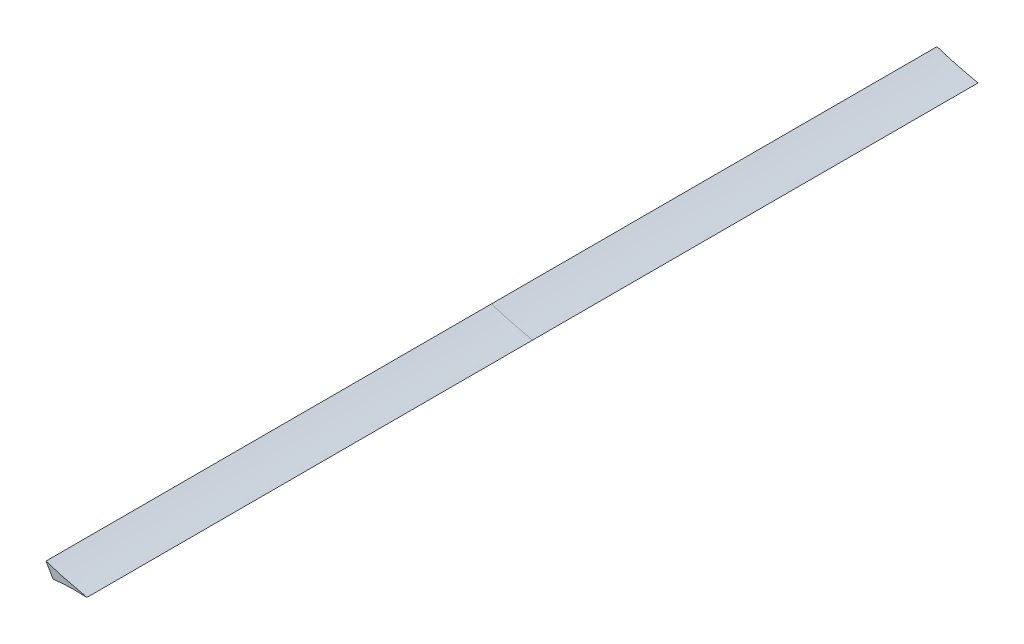
SolidWorks part; units mm, degrees
ref_plane "Front Plane" through (0, 0, 0) normal (0, 0, 1) x (1, 0, 0)
ref_plane "Top Plane" through (0, 0, 0) normal (0, 1, 0) x (1, 0, 0)
ref_plane "Right Plane" through (0, 0, 0) normal (1, 0, 0) x (0, 0, -1)
sketch "Sketch1" plane through (0, 0, 0) normal (0, 0, 1) x (1, 0, 0)
  line L0 (0, 0) -> (0, 6.4558)
  spline S0 degree 3 poles (0, 0) (0.1434, 0.0165) (1.156, 0.1322) (2.2016, 0.2452) (3.8964, 0.4173) (4.7503, 0.4989) (6.3146, 0.6383) (7.1135, 0.7047) (9.2324, 0.8592) (10.6247, 0.935) (13.1229, 1.0282) (14.2773, 1.055) (16.229, 1.0695) (17.0679, 1.0652) (18.5748, 1.0172) (19.2233, 0.9863) (19.9647, 0.9609) (20.1796, 0.9559) (20.6559, 0.9225) (20.7683, 0.9144) (20.6569, 0.9381) (20.1717, 1.0435) (19.963, 1.1073) (19.2301, 1.2999) (18.5794, 1.4369) (17.0647, 1.7643) (16.2324, 1.9523) (14.2778, 2.4036) (13.1319, 2.6753) (10.6235, 3.2908) (9.2465, 3.6428) (7.1171, 4.224) (6.3393, 4.4439) (4.7499, 4.9129) (3.051, 5.4372) (1.1998, 6.0477) (0.1682, 6.3983) (0, 6.4558) knots 0.902429 0.902429 0.902429 0.902429 0.904465 0.9168 0.917259 0.928487 0.928896 0.939398 0.939782 0.958877 0.95912 0.974883 0.974987 0.98705 0.987125 0.995254 0.995335 0.999481 0.999488 1 1.000528 1.000535 1.004807 1.004876 1.013224 1.013265 1.025673 1.025696 1.04199 1.042099 1.061953 1.062101 1.073248 1.073343 1.085462 1.09832 1.100826 1.100826 1.100826 1.100826
ref_plane "Plane1" through (0, 0, 450) normal (0, 0, 1) x (1, 0, 0)
sketch "Sketch2" plane through (0, 0, 0) normal (0, 1, 0) x (1, 0, 0)
  line L0 (0, 0) -> (-34.3096, -450)
  line L1 (-3.5976, -450) -> (3.5976, -450) construction
  line L2 (0, 0) -> (0, -450) construction
  dimension "D1" = 4.36
sketch "Sketch3" plane through (0, 0, 450) normal (0, 0, 1) x (1, 0, 0)
  line L0 (-34.3096, 0) -> (-34.3096, 2.1192)
  spline S0 degree 3 poles (-34.3096, 0) (-34.2523, 0.0055) (-33.8752, 0.0408) (-33.1944, 0.0953) (-32.2879, 0.1648) (-31.1949, 0.2467) (-29.9917, 0.2901) (-28.738, 0.3021) (-27.8235, 0.2832) (-27.1162, 0.2532) (-26.8769, 0.2319) (-26.667, 0.2236) (-26.8796, 0.267) (-27.1128, 0.3365) (-27.8244, 0.4814) (-28.7394, 0.673) (-29.993, 0.9563) (-31.1967, 1.2371) (-32.291, 1.5176) (-33.1962, 1.7795) (-33.8755, 1.9852) (-34.2523, 2.1014) (-34.3096, 2.1192) knots 0.902253 0.902253 0.902253 0.902253 0.904465 0.9168 0.928487 0.939398 0.958877 0.974883 0.98705 0.995254 0.999488 1 1.000528 1.004876 1.013265 1.025696 1.042099 1.062101 1.073343 1.085462 1.098303 1.100608 1.100608 1.100608 1.100608
extrude "Boss-Extrude1" add sketch "Sketch1" along normal blind 450
sketch "Sketch8" plane through (0, 0, 0) normal (0, 0, -1) x (-1, 0, 0)
  line L0 (0, 6.4558) -> (-3.5092, 0.3776)
  line L1 (-3.5092, 0.3776) -> (0, 0)
  line L2 (0, 0) -> (0, 6.4558)
  line L3 (0, 0) -> (0, 6.4558) construction
  spline S1 degree 3 poles (0, 0) (-0.1434, 0.0165) (-1.156, 0.1322) (-2.2016, 0.2452) (-3.8964, 0.4173) (-4.7503, 0.4989) (-6.3146, 0.6383) (-7.1135, 0.7047) (-9.2324, 0.8592) (-10.6247, 0.935) (-13.1229, 1.0282) (-14.2773, 1.055) (-16.229, 1.0695) (-17.0679, 1.0652) (-18.5748, 1.0172) (-19.2233, 0.9863) (-19.9647, 0.9609) (-20.1796, 0.9559) (-20.6559, 0.9225) (-20.7683, 0.9144) (-20.6569, 0.9381) (-20.1717, 1.0435) (-19.963, 1.1073) (-19.2301, 1.2999) (-18.5794, 1.4369) (-17.0647, 1.7643) (-16.2324, 1.9523) (-14.2778, 2.4036) (-13.1319, 2.6753) (-10.6235, 3.2908) (-9.2465, 3.6428) (-7.1171, 4.224) (-6.3393, 4.4439) (-4.7499, 4.9129) (-3.051, 5.4372) (-1.1998, 6.0477) (-0.1682, 6.3983) (0, 6.4558) knots 0.902429 0.902429 0.902429 0.902429 0.904465 0.9168 0.917259 0.928487 0.928896 0.939398 0.939782 0.958877 0.95912 0.974883 0.974987 0.98705 0.987125 0.995254 0.995335 0.999481 0.999488 1 1.000528 1.000535 1.004807 1.004876 1.013224 1.013265 1.025673 1.025696 1.04199 1.042099 1.061953 1.062101 1.073248 1.073343 1.085462 1.09832 1.100826 1.100826 1.100826 1.100826 construction
  point P3 (0, 0)
  point P4 (0, 0)
  point P5 (0, 0)
  point P8 (0, 0)
  point P11 (0, 0)
  point P12 (0, 0)
  point P13 (0, 0)
  dimension "D1" = 30
extrude "Cut-Extrude1" cut sketch "Sketch8" against normal blind 450
sketch "Sketch7" plane through (0, 0, 0) normal (0, 1, 0) x (1, 0, 0)
  line L0 (0, -450) -> (0, 0) construction
  line L3 (0, -225) -> (20.7127, -225)
  line L4 (20.7127, -450) -> (20.7127, 0) construction
  line L7 (20.7127, 0) -> (0, 0)
  line L8 (0, 0) -> (20.7127, 0) construction
  point P0 (0, -225)
  dimension "D1" = 225
split "Split1" trim tools "Sketch7" bodies to split 350 341 resulting bodies 351 352
